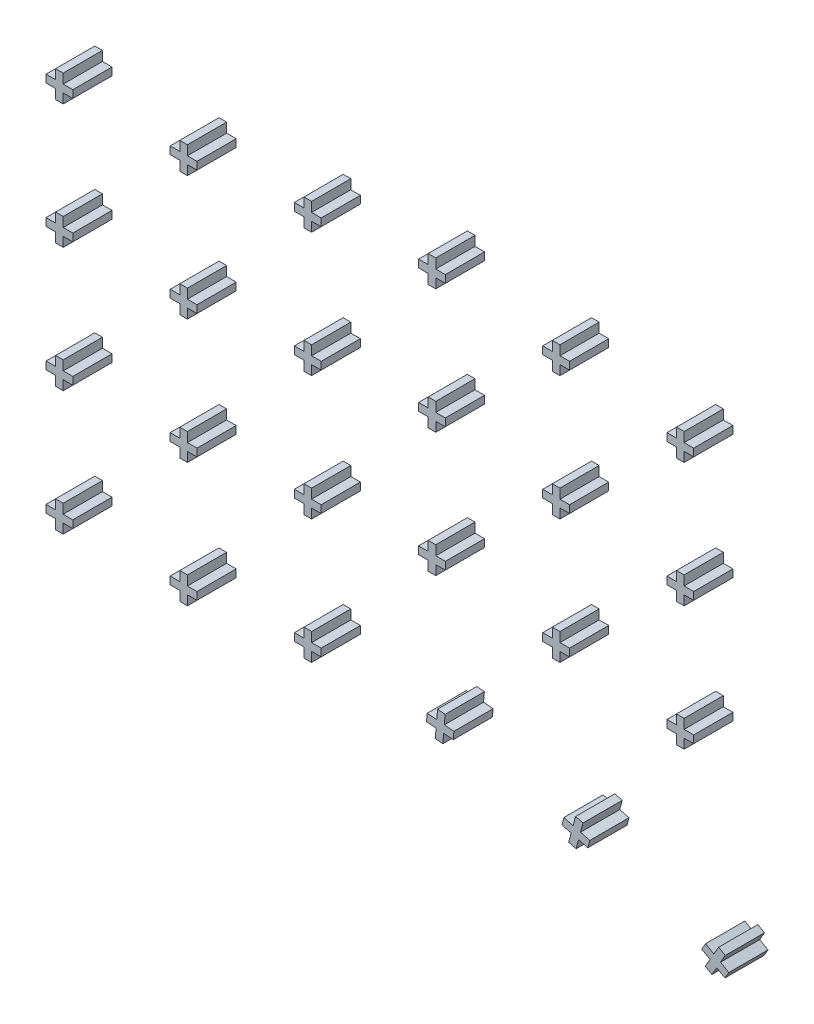
SolidWorks part; units mm, degrees
ref_plane "Front Plane" through (0, 0, 0) normal (0, 0, 1) x (1, 0, 0)
ref_plane "Top Plane" through (0, 0, 0) normal (0, 1, 0) x (1, 0, 0)
ref_plane "Right Plane" through (0, 0, 0) normal (1, 0, 0) x (0, 0, -1)
sketch "Sketch3" plane through (0, 0, 0) normal (0, 0, 1) x (1, 0, 0)
  line L0 (-5.8519, 4) -> (-5.8519, 23) construction
  line L1 (-5.8519, 23) -> (13.1481, 23) construction
  line L2 (13.1481, 23) -> (13.1481, 4) construction
  line L3 (-5.8519, 23) -> (13.1481, 4) construction
  line L4 (13.1481, -15) -> (-5.8519, -15) construction
  line L5 (13.1481, -15) -> (13.1481, 4) construction
  line L6 (13.1481, 4) -> (-5.8519, 4) construction
  line L7 (-5.8519, -15) -> (-5.8519, 4) construction
  line L8 (13.1481, -15) -> (-5.8519, 4) construction
  line L9 (-15.3519, 21) -> (-15.3519, 23) construction
  line L10 (22.6481, 21) -> (22.6481, 23) construction
  line L11 (13.1481, 23) -> (22.6481, 23) construction
  line L12 (-15.3519, 23) -> (-5.8519, 23) construction
  line L13 (13.1481, 21) -> (32.1481, 21) construction
  line L14 (32.1481, 2) -> (32.1481, -17) construction
  line L15 (32.1481, 2) -> (13.1481, 2) construction
  line L16 (32.1481, 2) -> (32.1481, 21) construction
  line L17 (32.1481, -17) -> (13.1481, -17) construction
  line L18 (13.1481, 2) -> (32.1481, -17) construction
  line L19 (32.1481, 2) -> (13.1481, 21) construction
  line L20 (32.1481, 19) -> (51.1481, 19) construction
  line L21 (51.1481, 19) -> (51.1481, 0) construction
  line L22 (-24.8519, -36) -> (-24.8519, -17) construction
  line L23 (32.1481, -36) -> (13.1481, -36) construction
  line L24 (-5.8519, -36) -> (-5.8519, -17) construction
  line L25 (13.1481, -17) -> (32.1481, -36) construction
  line L26 (51.1481, 0) -> (32.1481, 0) construction
  line L27 (32.1481, 19) -> (51.1481, 0) construction
  line L28 (51.1481, 0) -> (51.1481, -19) construction
  line L29 (51.1481, -19) -> (32.1481, -19) construction
  line L30 (51.1481, -19) -> (32.1481, 0) construction
  line L31 (51.1481, -19) -> (51.1481, -38) construction
  line L32 (51.1481, -38) -> (32.1481, -38) construction
  line L33 (51.1481, -38) -> (32.1481, -19) construction
  line L34 (-5.8519, -17) -> (-5.8519, -15) construction
  line L35 (-5.8519, -34) -> (13.1481, -34) construction
  line L36 (-5.8519, -15) -> (13.1481, -34) construction
  line L37 (41.6481, 19) -> (41.6481, 21) construction
  line L38 (41.6481, 21) -> (32.1481, 21) construction
  line L39 (-5.8519, 21) -> (-24.8519, 21) construction
  line L40 (-24.8519, 21) -> (-24.8519, 2) construction
  line L41 (-24.8519, 2) -> (-5.8519, 2) construction
  line L42 (-24.8519, 21) -> (-5.8519, 2) construction
  line L43 (-24.8519, 2) -> (-24.8519, -17) construction
  line L44 (-24.8519, -17) -> (-5.8519, -17) construction
  line L45 (-24.8519, 2) -> (-5.8519, -17) construction
  line L46 (-24.8519, -38) -> (-24.8519, -36) construction
  line L47 (-24.8519, -36) -> (-5.8519, -36) construction
  line L48 (-24.8519, 21) -> (-34.3519, 21) construction
  line L49 (-34.3519, 21) -> (-34.3519, 19) construction
  line L50 (-24.8519, 19) -> (-43.8519, 19) construction
  line L51 (-43.8519, 19) -> (-43.8519, 0) construction
  line L52 (-43.8519, 0) -> (-24.8519, 0) construction
  line L53 (-43.8519, 19) -> (-24.8519, 0) construction
  line L54 (-43.8519, 0) -> (-43.8519, -19) construction
  line L55 (-24.8519, -19) -> (-43.8519, -19) construction
  line L56 (-43.8519, 0) -> (-24.8519, -19) construction
  line L57 (-43.8519, -19) -> (-43.8519, -38) construction
  line L58 (-43.8519, -38) -> (-24.8519, -38) construction
  line L59 (-43.8519, -19) -> (-24.8519, -38) construction
  line L60 (-24.8519, -17) -> (-5.8519, -36) construction
  line L61 (-43.8519, 19) -> (-62.8519, 19) construction
  line L62 (-62.8519, 19) -> (-62.8519, 0) construction
  line L63 (-62.8519, 0) -> (-43.8519, 0) construction
  line L64 (-62.8519, 19) -> (-43.8519, 0) construction
  line L65 (-62.8519, 0) -> (-62.8519, -19) construction
  line L66 (-62.8519, -19) -> (-43.8519, -19) construction
  line L67 (-62.8519, 0) -> (-43.8519, -19) construction
  line L68 (-62.8519, -19) -> (-62.8519, -38) construction
  line L69 (-62.8519, -38) -> (-43.8519, -38) construction
  line L70 (-62.8519, -19) -> (-43.8519, -38) construction
  line L71 (32.1481, -36) -> (32.1481, -17) construction
  line L72 (32.1481, -38) -> (32.1481, -36) construction
  line L73 (13.1481, -36) -> (13.1481, -34) construction
  line L74 (13.1481, -15) -> (13.1481, -34) construction
  line L75 (-62.8519, -38) -> (-62.8519, -57) construction
  line L76 (-62.8519, -57) -> (-43.8519, -57) construction
  line L77 (-43.8519, -57) -> (-43.8519, -38) construction
  line L78 (-43.8519, -57) -> (-24.8519, -57) construction
  line L79 (-24.8519, -57) -> (-24.8519, -38) construction
  line L80 (-24.8519, -55) -> (-5.8519, -55) construction
  line L81 (-5.8519, -55) -> (-5.8519, -36) construction
  line L82 (-3.7261, -35.9013) -> (-5.3821, -54.829) construction
  line L83 (-5.3821, -54.829) -> (13.5456, -56.4849) construction
  line L84 (13.5456, -56.4849) -> (15.2016, -37.5572) construction
  line L85 (15.2016, -37.5572) -> (-3.7261, -35.9013) construction
  line L86 (-3.7261, -35.9013) -> (13.5456, -56.4849) construction
  line L87 (18.9497, -38.2475) -> (14.0322, -56.6001) construction
  line L88 (-5.8519, -55) -> (-5.3821, -54.829) construction
  line L89 (18.9497, -38.2475) -> (37.3023, -43.1651) construction
  line L90 (37.3023, -43.1651) -> (32.3848, -61.5177) construction
  line L91 (-24.8519, -36) -> (-5.8519, -55) construction
  line L92 (-43.8519, -38) -> (-24.8519, -57) construction
  line L93 (-62.8519, -38) -> (-43.8519, -57) construction
  line L94 (14.0322, -56.6001) -> (32.3848, -61.5177) construction
  line L95 (37.3023, -43.1651) -> (37.3023, -38) construction
  line L96 (18.9497, -38.2475) -> (32.3848, -61.5177) construction
  line L97 (32.833, -61.7393) -> (44.708, -41.1712) construction
  line L98 (44.708, -41.1712) -> (61.1625, -50.6712) construction
  line L99 (61.1625, -50.6712) -> (49.2875, -71.2393) construction
  line L100 (49.2875, -71.2393) -> (32.833, -61.7393) construction
  line L101 (44.708, -41.1712) -> (49.2875, -71.2393) construction
  line L102 (13.5456, -56.4849) -> (14.0322, -56.6001) construction
  line L103 (32.3848, -61.5177) -> (32.833, -61.7393) construction
  line L104 (15.2016, -37.5572) -> (15.2016, -36) construction
  line L105 (44.708, -41.1712) -> (44.708, -38) construction
  line L106 (-53.9369, 11.55) -> (-52.7669, 11.55)
  line L107 (-60.2769, 2.575) -> (-46.4269, 2.575) construction
  line L108 (-60.2769, 2.575) -> (-60.2769, 16.425) construction
  line L109 (-60.2769, 16.425) -> (-46.4269, 16.425) construction
  line L110 (-46.4269, 2.575) -> (-46.4269, 16.425) construction
  line L111 (-60.2769, 2.575) -> (-46.4269, 16.425) construction
  line L112 (-60.2769, 16.425) -> (-46.4269, 2.575) construction
  line L113 (-60.2769, -16.425) -> (-46.4269, -16.425) construction
  line L114 (-60.2769, -16.425) -> (-60.2769, -2.575) construction
  line L115 (-60.2769, -2.575) -> (-46.4269, -2.575) construction
  line L116 (-46.4269, -16.425) -> (-46.4269, -2.575) construction
  line L117 (-60.2769, -16.425) -> (-46.4269, -2.575) construction
  line L118 (-60.2769, -2.575) -> (-46.4269, -16.425) construction
  line L119 (-60.2769, -35.425) -> (-46.4269, -35.425) construction
  line L120 (-60.2769, -35.425) -> (-60.2769, -21.575) construction
  line L121 (-60.2769, -21.575) -> (-46.4269, -21.575) construction
  line L122 (-46.4269, -35.425) -> (-46.4269, -21.575) construction
  line L123 (-60.2769, -35.425) -> (-46.4269, -21.575) construction
  line L124 (-60.2769, -21.575) -> (-46.4269, -35.425) construction
  line L125 (-41.2769, 2.575) -> (-27.4269, 2.575) construction
  line L126 (-41.2769, 2.575) -> (-41.2769, 16.425) construction
  line L127 (-41.2769, 16.425) -> (-27.4269, 16.425) construction
  line L128 (-27.4269, 2.575) -> (-27.4269, 16.425) construction
  line L129 (-41.2769, 2.575) -> (-27.4269, 16.425) construction
  line L130 (-41.2769, 16.425) -> (-27.4269, 2.575) construction
  line L131 (-41.2769, -16.425) -> (-27.4269, -16.425) construction
  line L132 (-41.2769, -16.425) -> (-41.2769, -2.575) construction
  line L133 (-41.2769, -2.575) -> (-27.4269, -2.575) construction
  line L134 (-27.4269, -16.425) -> (-27.4269, -2.575) construction
  line L135 (-41.2769, -16.425) -> (-27.4269, -2.575) construction
  line L136 (-41.2769, -2.575) -> (-27.4269, -16.425) construction
  line L137 (-41.2769, -35.425) -> (-27.4269, -35.425) construction
  line L138 (-41.2769, -35.425) -> (-41.2769, -21.575) construction
  line L139 (-41.2769, -21.575) -> (-27.4269, -21.575) construction
  line L140 (-27.4269, -35.425) -> (-27.4269, -21.575) construction
  line L141 (-41.2769, -35.425) -> (-27.4269, -21.575) construction
  line L142 (-41.2769, -21.575) -> (-27.4269, -35.425) construction
  line L143 (-60.2769, -54.425) -> (-46.4269, -54.425) construction
  line L144 (-60.2769, -54.425) -> (-60.2769, -40.575) construction
  line L145 (-60.2769, -40.575) -> (-46.4269, -40.575) construction
  line L146 (-46.4269, -54.425) -> (-46.4269, -40.575) construction
  line L147 (-60.2769, -54.425) -> (-46.4269, -40.575) construction
  line L148 (-60.2769, -40.575) -> (-46.4269, -54.425) construction
  line L149 (-27.4269, -54.425) -> (-41.2769, -54.425) construction
  line L150 (-27.4269, -54.425) -> (-27.4269, -40.575) construction
  line L151 (-27.4269, -40.575) -> (-41.2769, -40.575) construction
  line L152 (-41.2769, -54.425) -> (-41.2769, -40.575) construction
  line L153 (-27.4269, -54.425) -> (-41.2769, -40.575) construction
  line L154 (-27.4269, -40.575) -> (-41.2769, -54.425) construction
  line L155 (-8.4269, -33.425) -> (-22.2769, -33.425) construction
  line L156 (-8.4269, -33.425) -> (-8.4269, -19.575) construction
  line L157 (-8.4269, -19.575) -> (-22.2769, -19.575) construction
  line L158 (-22.2769, -33.425) -> (-22.2769, -19.575) construction
  line L159 (-8.4269, -33.425) -> (-22.2769, -19.575) construction
  line L160 (-8.4269, -19.575) -> (-22.2769, -33.425) construction
  line L161 (-8.4269, -52.425) -> (-22.2769, -52.425) construction
  line L162 (-8.4269, -52.425) -> (-8.4269, -38.575) construction
  line L163 (-8.4269, -38.575) -> (-22.2769, -38.575) construction
  line L164 (-22.2769, -52.425) -> (-22.2769, -38.575) construction
  line L165 (-8.4269, -52.425) -> (-22.2769, -38.575) construction
  line L166 (-8.4269, -38.575) -> (-22.2769, -52.425) construction
  line L167 (10.5731, -31.425) -> (-3.2769, -31.425) construction
  line L168 (10.5731, -31.425) -> (10.5731, -17.575) construction
  line L169 (10.5731, -17.575) -> (-3.2769, -17.575) construction
  line L170 (-3.2769, -31.425) -> (-3.2769, -17.575) construction
  line L171 (10.5731, -31.425) -> (-3.2769, -17.575) construction
  line L172 (10.5731, -17.575) -> (-3.2769, -31.425) construction
  line L173 (-8.4269, -14.425) -> (-22.2769, -14.425) construction
  line L174 (-8.4269, -14.425) -> (-8.4269, -0.575) construction
  line L175 (-8.4269, -0.575) -> (-22.2769, -0.575) construction
  line L176 (-22.2769, -14.425) -> (-22.2769, -0.575) construction
  line L177 (-8.4269, -14.425) -> (-22.2769, -0.575) construction
  line L178 (-8.4269, -0.575) -> (-22.2769, -14.425) construction
  line L179 (-8.4269, 4.575) -> (-22.2769, 4.575) construction
  line L180 (-8.4269, 4.575) -> (-8.4269, 18.425) construction
  line L181 (-8.4269, 18.425) -> (-22.2769, 18.425) construction
  line L182 (-22.2769, 4.575) -> (-22.2769, 18.425) construction
  line L183 (-8.4269, 4.575) -> (-22.2769, 18.425) construction
  line L184 (-8.4269, 18.425) -> (-22.2769, 4.575) construction
  line L185 (29.5731, -33.425) -> (15.7231, -33.425) construction
  line L186 (29.5731, -33.425) -> (29.5731, -19.575) construction
  line L187 (29.5731, -19.575) -> (15.7231, -19.575) construction
  line L188 (15.7231, -33.425) -> (15.7231, -19.575) construction
  line L189 (29.5731, -33.425) -> (15.7231, -19.575) construction
  line L190 (29.5731, -19.575) -> (15.7231, -33.425) construction
  line L191 (29.5731, -14.425) -> (15.7231, -14.425) construction
  line L192 (29.5731, -14.425) -> (29.5731, -0.575) construction
  line L193 (29.5731, -0.575) -> (15.7231, -0.575) construction
  line L194 (15.7231, -14.425) -> (15.7231, -0.575) construction
  line L195 (29.5731, -14.425) -> (15.7231, -0.575) construction
  line L196 (29.5731, -0.575) -> (15.7231, -14.425) construction
  line L197 (10.5731, -12.425) -> (-3.2769, -12.425) construction
  line L198 (10.5731, -12.425) -> (10.5731, 1.425) construction
  line L199 (10.5731, 1.425) -> (-3.2769, 1.425) construction
  line L200 (-3.2769, -12.425) -> (-3.2769, 1.425) construction
  line L201 (10.5731, -12.425) -> (-3.2769, 1.425) construction
  line L202 (10.5731, 1.425) -> (-3.2769, -12.425) construction
  line L203 (10.5731, 6.575) -> (-3.2769, 6.575) construction
  line L204 (10.5731, 6.575) -> (10.5731, 20.425) construction
  line L205 (10.5731, 20.425) -> (-3.2769, 20.425) construction
  line L206 (-3.2769, 6.575) -> (-3.2769, 20.425) construction
  line L207 (10.5731, 6.575) -> (-3.2769, 20.425) construction
  line L208 (10.5731, 20.425) -> (-3.2769, 6.575) construction
  line L209 (29.5731, 4.575) -> (15.7231, 4.575) construction
  line L210 (29.5731, 4.575) -> (29.5731, 18.425) construction
  line L211 (29.5731, 18.425) -> (15.7231, 18.425) construction
  line L212 (15.7231, 4.575) -> (15.7231, 18.425) construction
  line L213 (29.5731, 4.575) -> (15.7231, 18.425) construction
  line L214 (29.5731, 18.425) -> (15.7231, 4.575) construction
  line L215 (48.5731, 2.575) -> (34.7231, 2.575) construction
  line L216 (48.5731, 2.575) -> (48.5731, 16.425) construction
  line L217 (48.5731, 16.425) -> (34.7231, 16.425) construction
  line L218 (34.7231, 2.575) -> (34.7231, 16.425) construction
  line L219 (48.5731, 2.575) -> (34.7231, 16.425) construction
  line L220 (48.5731, 16.425) -> (34.7231, 2.575) construction
  line L221 (48.5731, -16.425) -> (34.7231, -16.425) construction
  line L222 (48.5731, -16.425) -> (48.5731, -2.575) construction
  line L223 (48.5731, -2.575) -> (34.7231, -2.575) construction
  line L224 (34.7231, -16.425) -> (34.7231, -2.575) construction
  line L225 (48.5731, -16.425) -> (34.7231, -2.575) construction
  line L226 (48.5731, -2.575) -> (34.7231, -16.425) construction
  line L227 (48.5731, -35.425) -> (34.7231, -35.425) construction
  line L228 (48.5731, -35.425) -> (48.5731, -21.575) construction
  line L229 (48.5731, -21.575) -> (34.7231, -21.575) construction
  line L230 (34.7231, -35.425) -> (34.7231, -21.575) construction
  line L231 (48.5731, -35.425) -> (34.7231, -21.575) construction
  line L232 (48.5731, -21.575) -> (34.7231, -35.425) construction
  line L233 (11.2048, -53.6953) -> (-2.5925, -52.4882) construction
  line L234 (11.2048, -53.6953) -> (12.412, -39.898) construction
  line L235 (12.412, -39.898) -> (-1.3853, -38.6909) construction
  line L236 (-2.5925, -52.4882) -> (-1.3853, -38.6909) construction
  line L237 (11.2048, -53.6953) -> (-1.3853, -38.6909) construction
  line L238 (12.412, -39.898) -> (-2.5925, -52.4882) construction
  line L239 (30.564, -58.364) -> (17.1859, -54.7793) construction
  line L240 (30.564, -58.364) -> (34.1486, -44.9859) construction
  line L241 (34.1486, -44.9859) -> (20.7705, -41.4012) construction
  line L242 (17.1859, -54.7793) -> (20.7705, -41.4012) construction
  line L243 (30.564, -58.364) -> (20.7705, -41.4012) construction
  line L244 (34.1486, -44.9859) -> (17.1859, -54.7793) construction
  line L245 (49.5324, -65.665) -> (37.538, -58.74) construction
  line L246 (49.5324, -65.665) -> (56.4574, -53.6705) construction
  line L247 (56.4574, -53.6705) -> (44.463, -46.7455) construction
  line L248 (37.538, -58.74) -> (44.463, -46.7455) construction
  line L249 (49.5324, -65.665) -> (44.463, -46.7455) construction
  line L250 (56.4574, -53.6705) -> (37.538, -58.74) construction
  line L251 (-52.7669, 11.55) -> (-52.7669, 10.085)
  line L252 (4.5056, -44.0999) -> (5.6712, -44.2019)
  line L253 (5.6712, -44.2019) -> (5.5435, -45.6613)
  line L254 (5.5435, -45.6613) -> (7.0029, -45.789)
  line L255 (7.0029, -45.789) -> (6.901, -46.9546)
  line L256 (6.901, -46.9546) -> (5.4415, -46.8269)
  line L257 (5.4415, -46.8269) -> (5.3139, -48.2863)
  line L258 (5.3139, -48.2863) -> (4.1483, -48.1843)
  line L259 (4.1483, -48.1843) -> (4.276, -46.7249)
  line L260 (4.276, -46.7249) -> (2.8166, -46.5972)
  line L261 (2.8166, -46.5972) -> (2.9185, -45.4317)
  line L262 (2.9185, -45.4317) -> (4.378, -45.5594)
  line L263 (4.378, -45.5594) -> (4.5056, -44.0999)
  line L264 (4.378, -45.5594) -> (5.4415, -46.8269) construction
  line L265 (4.276, -46.7249) -> (5.5435, -45.6613) construction
  line L266 (-52.7669, 10.085) -> (-51.3019, 10.085)
  line L267 (-51.3019, 10.085) -> (-51.3019, 8.915)
  line L268 (-51.3019, 8.915) -> (-52.7669, 8.915)
  line L269 (-52.7669, 8.915) -> (-52.7669, 7.45)
  line L270 (-52.7669, 7.45) -> (-53.9369, 7.45)
  line L271 (-53.9369, 7.45) -> (-53.9369, 8.915)
  line L272 (-53.9369, 8.915) -> (-55.4019, 8.915)
  line L273 (-55.4019, 8.915) -> (-55.4019, 10.085)
  line L274 (-55.4019, 10.085) -> (-53.9369, 10.085)
  line L275 (-53.9369, 10.085) -> (-53.9369, 11.55)
  line L276 (-53.9369, 10.085) -> (-52.7669, 8.915) construction
  line L277 (-53.9369, 8.915) -> (-52.7669, 10.085) construction
  line L278 (-34.9369, 11.55) -> (-33.7669, 11.55)
  line L279 (-33.7669, 11.55) -> (-33.7669, 10.085)
  line L280 (-33.7669, 10.085) -> (-32.3019, 10.085)
  line L281 (-32.3019, 10.085) -> (-32.3019, 8.915)
  line L282 (-32.3019, 8.915) -> (-33.7669, 8.915)
  line L283 (-33.7669, 8.915) -> (-33.7669, 7.45)
  line L284 (-33.7669, 7.45) -> (-34.9369, 7.45)
  line L285 (-34.9369, 7.45) -> (-34.9369, 8.915)
  line L286 (-34.9369, 8.915) -> (-36.4019, 8.915)
  line L287 (-36.4019, 8.915) -> (-36.4019, 10.085)
  line L288 (-36.4019, 10.085) -> (-34.9369, 10.085)
  line L289 (-34.9369, 10.085) -> (-34.9369, 11.55)
  line L290 (-34.9369, 10.085) -> (-33.7669, 8.915) construction
  line L291 (-34.9369, 8.915) -> (-33.7669, 10.085) construction
  line L292 (-15.9369, 13.55) -> (-14.7669, 13.55)
  line L293 (-14.7669, 13.55) -> (-14.7669, 12.085)
  line L294 (-14.7669, 12.085) -> (-13.3019, 12.085)
  line L295 (-13.3019, 12.085) -> (-13.3019, 10.915)
  line L296 (-13.3019, 10.915) -> (-14.7669, 10.915)
  line L297 (-14.7669, 10.915) -> (-14.7669, 9.45)
  line L298 (-14.7669, 9.45) -> (-15.9369, 9.45)
  line L299 (-15.9369, 9.45) -> (-15.9369, 10.915)
  line L300 (-15.9369, 10.915) -> (-17.4019, 10.915)
  line L301 (-17.4019, 10.915) -> (-17.4019, 12.085)
  line L302 (-17.4019, 12.085) -> (-15.9369, 12.085)
  line L303 (-15.9369, 12.085) -> (-15.9369, 13.55)
  line L304 (-15.9369, 12.085) -> (-14.7669, 10.915) construction
  line L305 (-15.9369, 10.915) -> (-14.7669, 12.085) construction
  line L306 (3.0631, 15.55) -> (4.2331, 15.55)
  line L307 (4.2331, 15.55) -> (4.2331, 14.085)
  line L308 (4.2331, 14.085) -> (5.6981, 14.085)
  line L309 (5.6981, 14.085) -> (5.6981, 12.915)
  line L310 (5.6981, 12.915) -> (4.2331, 12.915)
  line L311 (4.2331, 12.915) -> (4.2331, 11.45)
  line L312 (4.2331, 11.45) -> (3.0631, 11.45)
  line L313 (3.0631, 11.45) -> (3.0631, 12.915)
  line L314 (3.0631, 12.915) -> (1.5981, 12.915)
  line L315 (1.5981, 12.915) -> (1.5981, 14.085)
  line L316 (1.5981, 14.085) -> (3.0631, 14.085)
  line L317 (3.0631, 14.085) -> (3.0631, 15.55)
  line L318 (3.0631, 14.085) -> (4.2331, 12.915) construction
  line L319 (3.0631, 12.915) -> (4.2331, 14.085) construction
  line L320 (22.0631, 13.55) -> (23.2331, 13.55)
  line L321 (23.2331, 13.55) -> (23.2331, 12.085)
  line L322 (23.2331, 12.085) -> (24.6981, 12.085)
  line L323 (24.6981, 12.085) -> (24.6981, 10.915)
  line L324 (24.6981, 10.915) -> (23.2331, 10.915)
  line L325 (23.2331, 10.915) -> (23.2331, 9.45)
  line L326 (23.2331, 9.45) -> (22.0631, 9.45)
  line L327 (22.0631, 9.45) -> (22.0631, 10.915)
  line L328 (22.0631, 10.915) -> (20.5981, 10.915)
  line L329 (20.5981, 10.915) -> (20.5981, 12.085)
  line L330 (20.5981, 12.085) -> (22.0631, 12.085)
  line L331 (22.0631, 12.085) -> (22.0631, 13.55)
  line L332 (22.0631, 12.085) -> (23.2331, 10.915) construction
  line L333 (22.0631, 10.915) -> (23.2331, 12.085) construction
  line L334 (22.0631, -5.45) -> (23.2331, -5.45)
  line L335 (23.2331, -5.45) -> (23.2331, -6.915)
  line L336 (23.2331, -6.915) -> (24.6981, -6.915)
  line L337 (24.6981, -6.915) -> (24.6981, -8.085)
  line L338 (24.6981, -8.085) -> (23.2331, -8.085)
  line L339 (23.2331, -8.085) -> (23.2331, -9.55)
  line L340 (23.2331, -9.55) -> (22.0631, -9.55)
  line L341 (22.0631, -9.55) -> (22.0631, -8.085)
  line L342 (22.0631, -8.085) -> (20.5981, -8.085)
  line L343 (20.5981, -8.085) -> (20.5981, -6.915)
  line L344 (20.5981, -6.915) -> (22.0631, -6.915)
  line L345 (22.0631, -6.915) -> (22.0631, -5.45)
  line L346 (22.0631, -6.915) -> (23.2331, -8.085) construction
  line L347 (22.0631, -8.085) -> (23.2331, -6.915) construction
  line L348 (3.0631, -3.45) -> (4.2331, -3.45)
  line L349 (4.2331, -3.45) -> (4.2331, -4.915)
  line L350 (4.2331, -4.915) -> (5.6981, -4.915)
  line L351 (5.6981, -4.915) -> (5.6981, -6.085)
  line L352 (5.6981, -6.085) -> (4.2331, -6.085)
  line L353 (4.2331, -6.085) -> (4.2331, -7.55)
  line L354 (4.2331, -7.55) -> (3.0631, -7.55)
  line L355 (3.0631, -7.55) -> (3.0631, -6.085)
  line L356 (3.0631, -6.085) -> (1.5981, -6.085)
  line L357 (1.5981, -6.085) -> (1.5981, -4.915)
  line L358 (1.5981, -4.915) -> (3.0631, -4.915)
  line L359 (3.0631, -4.915) -> (3.0631, -3.45)
  line L360 (3.0631, -4.915) -> (4.2331, -6.085) construction
  line L361 (3.0631, -6.085) -> (4.2331, -4.915) construction
  line L362 (-15.9369, -5.45) -> (-14.7669, -5.45)
  line L363 (-14.7669, -5.45) -> (-14.7669, -6.915)
  line L364 (-14.7669, -6.915) -> (-13.3019, -6.915)
  line L365 (-13.3019, -6.915) -> (-13.3019, -8.085)
  line L366 (-13.3019, -8.085) -> (-14.7669, -8.085)
  line L367 (-14.7669, -8.085) -> (-14.7669, -9.55)
  line L368 (-14.7669, -9.55) -> (-15.9369, -9.55)
  line L369 (-15.9369, -9.55) -> (-15.9369, -8.085)
  line L370 (-15.9369, -8.085) -> (-17.4019, -8.085)
  line L371 (-17.4019, -8.085) -> (-17.4019, -6.915)
  line L372 (-17.4019, -6.915) -> (-15.9369, -6.915)
  line L373 (-15.9369, -6.915) -> (-15.9369, -5.45)
  line L374 (-15.9369, -6.915) -> (-14.7669, -8.085) construction
  line L375 (-15.9369, -8.085) -> (-14.7669, -6.915) construction
  line L376 (3.0631, -22.45) -> (4.2331, -22.45)
  line L377 (4.2331, -22.45) -> (4.2331, -23.915)
  line L378 (4.2331, -23.915) -> (5.6981, -23.915)
  line L379 (5.6981, -23.915) -> (5.6981, -25.085)
  line L380 (5.6981, -25.085) -> (4.2331, -25.085)
  line L381 (4.2331, -25.085) -> (4.2331, -26.55)
  line L382 (4.2331, -26.55) -> (3.0631, -26.55)
  line L383 (3.0631, -26.55) -> (3.0631, -25.085)
  line L384 (3.0631, -25.085) -> (1.5981, -25.085)
  line L385 (1.5981, -25.085) -> (1.5981, -23.915)
  line L386 (1.5981, -23.915) -> (3.0631, -23.915)
  line L387 (3.0631, -23.915) -> (3.0631, -22.45)
  line L388 (3.0631, -23.915) -> (4.2331, -25.085) construction
  line L389 (3.0631, -25.085) -> (4.2331, -23.915) construction
  line L390 (-15.9369, -24.45) -> (-14.7669, -24.45)
  line L391 (-14.7669, -24.45) -> (-14.7669, -25.915)
  line L392 (-14.7669, -25.915) -> (-13.3019, -25.915)
  line L393 (-13.3019, -25.915) -> (-13.3019, -27.085)
  line L394 (-13.3019, -27.085) -> (-14.7669, -27.085)
  line L395 (-14.7669, -27.085) -> (-14.7669, -28.55)
  line L396 (-14.7669, -28.55) -> (-15.9369, -28.55)
  line L397 (-15.9369, -28.55) -> (-15.9369, -27.085)
  line L398 (-15.9369, -27.085) -> (-17.4019, -27.085)
  line L399 (-17.4019, -27.085) -> (-17.4019, -25.915)
  line L400 (-17.4019, -25.915) -> (-15.9369, -25.915)
  line L401 (-15.9369, -25.915) -> (-15.9369, -24.45)
  line L402 (-15.9369, -25.915) -> (-14.7669, -27.085) construction
  line L403 (-15.9369, -27.085) -> (-14.7669, -25.915) construction
  line L404 (-34.9369, -7.45) -> (-33.7669, -7.45)
  line L405 (-33.7669, -7.45) -> (-33.7669, -8.915)
  line L406 (-33.7669, -8.915) -> (-32.3019, -8.915)
  line L407 (-32.3019, -8.915) -> (-32.3019, -10.085)
  line L408 (-32.3019, -10.085) -> (-33.7669, -10.085)
  line L409 (-33.7669, -10.085) -> (-33.7669, -11.55)
  line L410 (-33.7669, -11.55) -> (-34.9369, -11.55)
  line L411 (-34.9369, -11.55) -> (-34.9369, -10.085)
  line L412 (-34.9369, -10.085) -> (-36.4019, -10.085)
  line L413 (-36.4019, -10.085) -> (-36.4019, -8.915)
  line L414 (-36.4019, -8.915) -> (-34.9369, -8.915)
  line L415 (-34.9369, -8.915) -> (-34.9369, -7.45)
  line L416 (-34.9369, -8.915) -> (-33.7669, -10.085) construction
  line L417 (-34.9369, -10.085) -> (-33.7669, -8.915) construction
  line L418 (-53.9369, -7.45) -> (-52.7669, -7.45)
  line L419 (-52.7669, -7.45) -> (-52.7669, -8.915)
  line L420 (-52.7669, -8.915) -> (-51.3019, -8.915)
  line L421 (-51.3019, -8.915) -> (-51.3019, -10.085)
  line L422 (-51.3019, -10.085) -> (-52.7669, -10.085)
  line L423 (-52.7669, -10.085) -> (-52.7669, -11.55)
  line L424 (-52.7669, -11.55) -> (-53.9369, -11.55)
  line L425 (-53.9369, -11.55) -> (-53.9369, -10.085)
  line L426 (-53.9369, -10.085) -> (-55.4019, -10.085)
  line L427 (-55.4019, -10.085) -> (-55.4019, -8.915)
  line L428 (-55.4019, -8.915) -> (-53.9369, -8.915)
  line L429 (-53.9369, -8.915) -> (-53.9369, -7.45)
  line L430 (-53.9369, -8.915) -> (-52.7669, -10.085) construction
  line L431 (-53.9369, -10.085) -> (-52.7669, -8.915) construction
  line L432 (-53.9369, -26.45) -> (-52.7669, -26.45)
  line L433 (-52.7669, -26.45) -> (-52.7669, -27.915)
  line L434 (-52.7669, -27.915) -> (-51.3019, -27.915)
  line L435 (-51.3019, -27.915) -> (-51.3019, -29.085)
  line L436 (-51.3019, -29.085) -> (-52.7669, -29.085)
  line L437 (-52.7669, -29.085) -> (-52.7669, -30.55)
  line L438 (-52.7669, -30.55) -> (-53.9369, -30.55)
  line L439 (-53.9369, -30.55) -> (-53.9369, -29.085)
  line L440 (-53.9369, -29.085) -> (-55.4019, -29.085)
  line L441 (-55.4019, -29.085) -> (-55.4019, -27.915)
  line L442 (-55.4019, -27.915) -> (-53.9369, -27.915)
  line L443 (-53.9369, -27.915) -> (-53.9369, -26.45)
  line L444 (-53.9369, -27.915) -> (-52.7669, -29.085) construction
  line L445 (-53.9369, -29.085) -> (-52.7669, -27.915) construction
  line L446 (-34.9369, -26.45) -> (-33.7669, -26.45)
  line L447 (-33.7669, -26.45) -> (-33.7669, -27.915)
  line L448 (-33.7669, -27.915) -> (-32.3019, -27.915)
  line L449 (-32.3019, -27.915) -> (-32.3019, -29.085)
  line L450 (-32.3019, -29.085) -> (-33.7669, -29.085)
  line L451 (-33.7669, -29.085) -> (-33.7669, -30.55)
  line L452 (-33.7669, -30.55) -> (-34.9369, -30.55)
  line L453 (-34.9369, -30.55) -> (-34.9369, -29.085)
  line L454 (-34.9369, -29.085) -> (-36.4019, -29.085)
  line L455 (-36.4019, -29.085) -> (-36.4019, -27.915)
  line L456 (-36.4019, -27.915) -> (-34.9369, -27.915)
  line L457 (-34.9369, -27.915) -> (-34.9369, -26.45)
  line L458 (-34.9369, -27.915) -> (-33.7669, -29.085) construction
  line L459 (-34.9369, -29.085) -> (-33.7669, -27.915) construction
  line L460 (-53.9369, -45.45) -> (-52.7669, -45.45)
  line L461 (-52.7669, -45.45) -> (-52.7669, -46.915)
  line L462 (-52.7669, -46.915) -> (-51.3019, -46.915)
  line L463 (-51.3019, -46.915) -> (-51.3019, -48.085)
  line L464 (-51.3019, -48.085) -> (-52.7669, -48.085)
  line L465 (-52.7669, -48.085) -> (-52.7669, -49.55)
  line L466 (-52.7669, -49.55) -> (-53.9369, -49.55)
  line L467 (-53.9369, -49.55) -> (-53.9369, -48.085)
  line L468 (-53.9369, -48.085) -> (-55.4019, -48.085)
  line L469 (-55.4019, -48.085) -> (-55.4019, -46.915)
  line L470 (-55.4019, -46.915) -> (-53.9369, -46.915)
  line L471 (-53.9369, -46.915) -> (-53.9369, -45.45)
  line L472 (-53.9369, -46.915) -> (-52.7669, -48.085) construction
  line L473 (-53.9369, -48.085) -> (-52.7669, -46.915) construction
  line L474 (-34.9369, -45.45) -> (-33.7669, -45.45)
  line L475 (-33.7669, -45.45) -> (-33.7669, -46.915)
  line L476 (-33.7669, -46.915) -> (-32.3019, -46.915)
  line L477 (-32.3019, -46.915) -> (-32.3019, -48.085)
  line L478 (-32.3019, -48.085) -> (-33.7669, -48.085)
  line L479 (-33.7669, -48.085) -> (-33.7669, -49.55)
  line L480 (-33.7669, -49.55) -> (-34.9369, -49.55)
  line L481 (-34.9369, -49.55) -> (-34.9369, -48.085)
  line L482 (-34.9369, -48.085) -> (-36.4019, -48.085)
  line L483 (-36.4019, -48.085) -> (-36.4019, -46.915)
  line L484 (-36.4019, -46.915) -> (-34.9369, -46.915)
  line L485 (-34.9369, -46.915) -> (-34.9369, -45.45)
  line L486 (-34.9369, -46.915) -> (-33.7669, -48.085) construction
  line L487 (-34.9369, -48.085) -> (-33.7669, -46.915) construction
  line L488 (-15.9369, -43.45) -> (-14.7669, -43.45)
  line L489 (-14.7669, -43.45) -> (-14.7669, -44.915)
  line L490 (-14.7669, -44.915) -> (-13.3019, -44.915)
  line L491 (-13.3019, -44.915) -> (-13.3019, -46.085)
  line L492 (-13.3019, -46.085) -> (-14.7669, -46.085)
  line L493 (-14.7669, -46.085) -> (-14.7669, -47.55)
  line L494 (-14.7669, -47.55) -> (-15.9369, -47.55)
  line L495 (-15.9369, -47.55) -> (-15.9369, -46.085)
  line L496 (-15.9369, -46.085) -> (-17.4019, -46.085)
  line L497 (-17.4019, -46.085) -> (-17.4019, -44.915)
  line L498 (-17.4019, -44.915) -> (-15.9369, -44.915)
  line L499 (-15.9369, -44.915) -> (-15.9369, -43.45)
  line L500 (-15.9369, -44.915) -> (-14.7669, -46.085) construction
  line L501 (-15.9369, -46.085) -> (-14.7669, -44.915) construction
  line L502 (25.6328, -47.751) -> (26.7629, -48.0539)
  line L503 (26.7629, -48.0539) -> (26.3837, -49.4689)
  line L504 (26.3837, -49.4689) -> (27.7988, -49.8481)
  line L505 (27.7988, -49.8481) -> (27.496, -50.9782)
  line L506 (27.496, -50.9782) -> (26.0809, -50.5991)
  line L507 (26.0809, -50.5991) -> (25.7017, -52.0142)
  line L508 (25.7017, -52.0142) -> (24.5716, -51.7113)
  line L509 (24.5716, -51.7113) -> (24.9508, -50.2963)
  line L510 (24.9508, -50.2963) -> (23.5357, -49.9171)
  line L511 (23.5357, -49.9171) -> (23.8385, -48.787)
  line L512 (23.8385, -48.787) -> (25.2536, -49.1661)
  line L513 (25.2536, -49.1661) -> (25.6328, -47.751)
  line L514 (25.2536, -49.1661) -> (26.0809, -50.5991) construction
  line L515 (24.9508, -50.2963) -> (26.3837, -49.4689) construction
  line L516 (22.0631, -24.45) -> (23.2331, -24.45)
  line L517 (23.2331, -24.45) -> (23.2331, -25.915)
  line L518 (23.2331, -25.915) -> (24.6981, -25.915)
  line L519 (24.6981, -25.915) -> (24.6981, -27.085)
  line L520 (24.6981, -27.085) -> (23.2331, -27.085)
  line L521 (23.2331, -27.085) -> (23.2331, -28.55)
  line L522 (23.2331, -28.55) -> (22.0631, -28.55)
  line L523 (22.0631, -28.55) -> (22.0631, -27.085)
  line L524 (22.0631, -27.085) -> (20.5981, -27.085)
  line L525 (20.5981, -27.085) -> (20.5981, -25.915)
  line L526 (20.5981, -25.915) -> (22.0631, -25.915)
  line L527 (22.0631, -25.915) -> (22.0631, -24.45)
  line L528 (22.0631, -25.915) -> (23.2331, -27.085) construction
  line L529 (22.0631, -27.085) -> (23.2331, -25.915) construction
  line L530 (41.0631, -7.45) -> (42.2331, -7.45)
  line L531 (42.2331, -7.45) -> (42.2331, -8.915)
  line L532 (42.2331, -8.915) -> (43.6981, -8.915)
  line L533 (43.6981, -8.915) -> (43.6981, -10.085)
  line L534 (43.6981, -10.085) -> (42.2331, -10.085)
  line L535 (42.2331, -10.085) -> (42.2331, -11.55)
  line L536 (42.2331, -11.55) -> (41.0631, -11.55)
  line L537 (41.0631, -11.55) -> (41.0631, -10.085)
  line L538 (41.0631, -10.085) -> (39.5981, -10.085)
  line L539 (39.5981, -10.085) -> (39.5981, -8.915)
  line L540 (39.5981, -8.915) -> (41.0631, -8.915)
  line L541 (41.0631, -8.915) -> (41.0631, -7.45)
  line L542 (41.0631, -8.915) -> (42.2331, -10.085) construction
  line L543 (41.0631, -10.085) -> (42.2331, -8.915) construction
  line L544 (41.0631, 11.55) -> (42.2331, 11.55)
  line L545 (42.2331, 11.55) -> (42.2331, 10.085)
  line L546 (42.2331, 10.085) -> (43.6981, 10.085)
  line L547 (43.6981, 10.085) -> (43.6981, 8.915)
  line L548 (43.6981, 8.915) -> (42.2331, 8.915)
  line L549 (42.2331, 8.915) -> (42.2331, 7.45)
  line L550 (42.2331, 7.45) -> (41.0631, 7.45)
  line L551 (41.0631, 7.45) -> (41.0631, 8.915)
  line L552 (41.0631, 8.915) -> (39.5981, 8.915)
  line L553 (39.5981, 8.915) -> (39.5981, 10.085)
  line L554 (39.5981, 10.085) -> (41.0631, 10.085)
  line L555 (41.0631, 10.085) -> (41.0631, 11.55)
  line L556 (41.0631, 10.085) -> (42.2331, 8.915) construction
  line L557 (41.0631, 8.915) -> (42.2331, 10.085) construction
  line L558 (41.0631, -26.45) -> (42.2331, -26.45)
  line L559 (42.2331, -26.45) -> (42.2331, -27.915)
  line L560 (42.2331, -27.915) -> (43.6981, -27.915)
  line L561 (43.6981, -27.915) -> (43.6981, -29.085)
  line L562 (43.6981, -29.085) -> (42.2331, -29.085)
  line L563 (42.2331, -29.085) -> (42.2331, -30.55)
  line L564 (42.2331, -30.55) -> (41.0631, -30.55)
  line L565 (41.0631, -30.55) -> (41.0631, -29.085)
  line L566 (41.0631, -29.085) -> (39.5981, -29.085)
  line L567 (39.5981, -29.085) -> (39.5981, -27.915)
  line L568 (39.5981, -27.915) -> (41.0631, -27.915)
  line L569 (41.0631, -27.915) -> (41.0631, -26.45)
  line L570 (41.0631, -27.915) -> (42.2331, -29.085) construction
  line L571 (41.0631, -29.085) -> (42.2331, -27.915) construction
  line L572 (47.5161, -54.1374) -> (48.5293, -54.7224)
  line L573 (48.5293, -54.7224) -> (47.7968, -55.9911)
  line L574 (47.7968, -55.9911) -> (49.0656, -56.7236)
  line L575 (49.0656, -56.7236) -> (48.4806, -57.7369)
  line L576 (48.4806, -57.7369) -> (47.2118, -57.0044)
  line L577 (47.2118, -57.0044) -> (46.4793, -58.2731)
  line L578 (46.4793, -58.2731) -> (45.4661, -57.6881)
  line L579 (45.4661, -57.6881) -> (46.1986, -56.4194)
  line L580 (46.1986, -56.4194) -> (44.9299, -55.6869)
  line L581 (44.9299, -55.6869) -> (45.5149, -54.6736)
  line L582 (45.5149, -54.6736) -> (46.7836, -55.4061)
  line L583 (46.7836, -55.4061) -> (47.5161, -54.1374)
  line L584 (46.7836, -55.4061) -> (47.2118, -57.0044) construction
  line L585 (46.1986, -56.4194) -> (47.7968, -55.9911) construction
  point P64 (-53.3519, 9.5)
  point P78 (-53.3519, -9.5)
  point P83 (-53.3519, -28.5)
  point P88 (-34.3519, 9.5)
  point P93 (-34.3519, -9.5)
  point P98 (-34.3519, -28.5)
  point P103 (-53.3519, -47.5)
  point P108 (-34.3519, -47.5)
  point P113 (-15.3519, -26.5)
  point P118 (-15.3519, -45.5)
  point P123 (3.6481, -24.5)
  point P128 (-15.3519, -7.5)
  point P133 (-15.3519, 11.5)
  point P138 (22.6481, -26.5)
  point P143 (22.6481, -7.5)
  point P148 (3.6481, -5.5)
  point P153 (3.6481, 13.5)
  point P158 (22.6481, 11.5)
  point P163 (41.6481, 9.5)
  point P168 (41.6481, -9.5)
  point P173 (41.6481, -28.5)
  point P178 (4.9098, -46.1931)
  point P183 (46.9977, -56.2052)
  point P185 (25.6673, -49.8826)
  point P193 (4.9098, -46.1931)
  point P194 (-53.3519, 9.5)
  point P210 (4.9098, -46.1931)
  point P220 (-53.3519, 9.5)
  point P222 (-34.3519, 9.5)
  point P235 (-34.3519, 9.5)
  point P236 (-15.3519, 11.5)
  point P249 (-15.3519, 11.5)
  point P250 (3.6481, 13.5)
  point P263 (3.6481, 13.5)
  point P264 (22.6481, 11.5)
  point P277 (22.6481, 11.5)
  point P278 (22.6481, -7.5)
  point P291 (22.6481, -7.5)
  point P292 (3.6481, -5.5)
  point P305 (3.6481, -5.5)
  point P306 (-15.3519, -7.5)
  point P319 (-15.3519, -7.5)
  point P320 (3.6481, -24.5)
  point P333 (3.6481, -24.5)
  point P334 (-15.3519, -26.5)
  point P347 (-15.3519, -26.5)
  point P348 (-34.3519, -9.5)
  point P361 (-34.3519, -9.5)
  point P362 (-53.3519, -9.5)
  point P375 (-53.3519, -9.5)
  point P376 (-53.3519, -28.5)
  point P389 (-53.3519, -28.5)
  point P390 (-34.3519, -28.5)
  point P403 (-34.3519, -28.5)
  point P404 (-53.3519, -47.5)
  point P417 (-53.3519, -47.5)
  point P418 (-34.3519, -47.5)
  point P431 (-34.3519, -47.5)
  point P432 (-15.3519, -45.5)
  point P445 (-15.3519, -45.5)
  point P446 (-53.3519, -28.5)
  point P449 (25.6673, -49.8826)
  point P460 (22.6481, -26.5)
  point P473 (22.6481, -26.5)
  point P474 (41.6481, -9.5)
  point P487 (41.6481, -9.5)
  point P488 (41.6481, 9.5)
  point P501 (41.6481, 9.5)
  point P502 (41.6481, -28.5)
  point P515 (41.6481, -28.5)
  point P518 (25.6673, -49.8826)
  point P519 (46.9977, -56.2052)
  point P532 (46.9977, -56.2052)
  dimension "D1" = 19
  dimension "D2" = 2
  dimension "D4" = 23.75
  dimension "D5" = 5
  dimension "D6" = 10
  dimension "D7" = 15
  dimension "D8" = 13.316
  dimension "D9" = 26.311
  dimension "D10" = 0.5
  dimension "D11" = 13.85
  dimension "D12" = 1.17
  dimension "D13" = 4.1
  dimension "D14" = 1.17
  dimension "D15" = 4.1
  dimension "D16" = 1.17
  dimension "D17" = 4.1
  dimension "D18" = 1.17
  dimension "D19" = 4.1
  dimension "D20" = 1.17
  dimension "D21" = 4.1
  dimension "D22" = 1.17
  dimension "D23" = 4.1
  dimension "D24" = 1.17
  dimension "D25" = 4.1
  dimension "D26" = 1.17
  dimension "D27" = 4.1
  dimension "D28" = 1.17
  dimension "D29" = 4.1
  dimension "D30" = 1.17
  dimension "D31" = 4.1
  dimension "D32" = 1.17
  dimension "D33" = 4.1
  dimension "D34" = 1.17
  dimension "D35" = 4.1
  dimension "D36" = 1.17
  dimension "D37" = 4.1
  dimension "D38" = 1.17
  dimension "D39" = 4.1
  dimension "D40" = 1.17
  dimension "D41" = 4.1
  dimension "D42" = 1.17
  dimension "D43" = 4.1
  dimension "D44" = 1.17
  dimension "D45" = 4.1
  dimension "D46" = 1.17
  dimension "D47" = 4.1
  dimension "D48" = 1.17
  dimension "D49" = 4.1
  dimension "D50" = 1.17
  dimension "D51" = 4.1
  dimension "D52" = 1.17
  dimension "D53" = 4.1
  dimension "D54" = 1.17
  dimension "D55" = 4.1
  dimension "D56" = 1.17
  dimension "D57" = 4.1
  dimension "D58" = 1.17
  dimension "D59" = 4.1
  dimension "D60" = 200
extrude "Boss-Extrude1" add sketch "Sketch3" along normal blind 6
